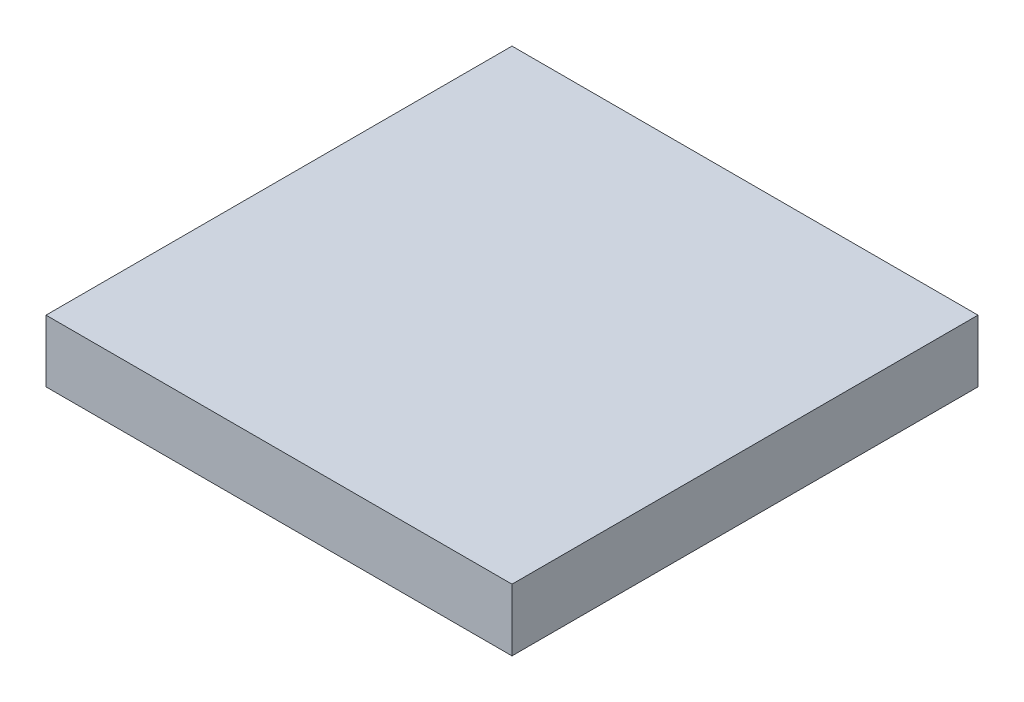
SolidWorks part; units mm, degrees
ref_plane "Front Plane" through (0, 0, 0) normal (0, 0, 1) x (1, 0, 0)
ref_plane "Top Plane" through (0, 0, 0) normal (0, 1, 0) x (1, 0, 0)
ref_plane "Right Plane" through (0, 0, 0) normal (1, 0, 0) x (0, 0, -1)
sketch "Sketch1" plane through (0, 0, 0) normal (0, 1, 0) x (1, 0, 0)
  line L1 (375, -375) -> (-375, -375)
  line L2 (375, -375) -> (375, 375)
  line L3 (375, 375) -> (-375, 375)
  line L4 (-375, -375) -> (-375, 375)
  line L5 (375, -375) -> (-375, 375) construction
  line L6 (375, 375) -> (-375, -375) construction
  point P0 (0, 0)
  dimension "D1" = 750
  dimension "D2" = 750
extrude "Boss-Extrude1" add sketch "Sketch1" along normal blind 100
sketch "Sketch3" plane through (0, 0, 0) normal (0, -1, 0) x (1, 0, 0)
  line L1 (300, -300) -> (-300, -300)
  line L2 (300, -300) -> (300, 300)
  line L3 (300, 300) -> (-300, 300)
  line L4 (-300, -300) -> (-300, 300)
  line L5 (300, -300) -> (-300, 300) construction
  line L6 (300, 300) -> (-300, -300) construction
  point P0 (0, 0)
  dimension "D1" = 600
  dimension "D2" = 600
extrude "Cut-Extrude2" cut sketch "Sketch3" against normal blind 50
